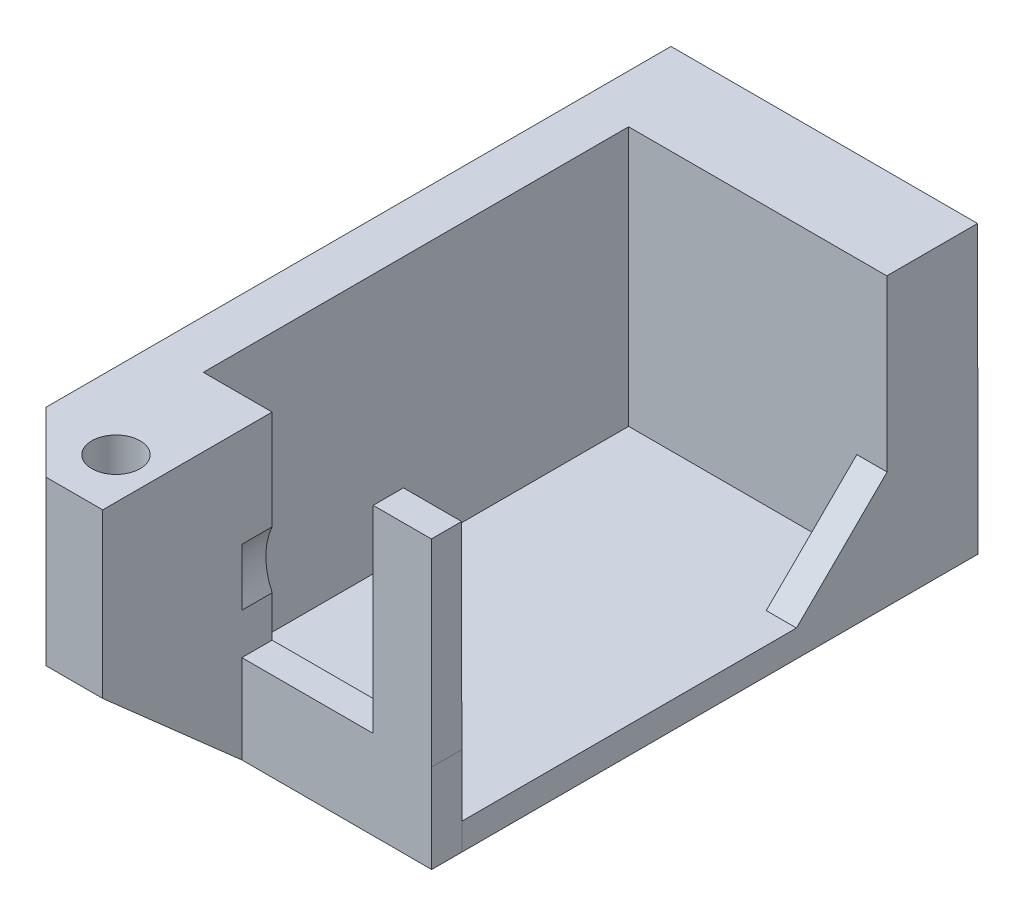
SolidWorks part; units mm, degrees
ref_plane "Alzado" through (0, 0, 0) normal (0, 0, 1) x (1, 0, 0)
ref_plane "Planta" through (0, 0, 0) normal (0, 1, 0) x (1, 0, 0)
ref_plane "Vista lateral" through (0, 0, 0) normal (1, 0, 0) x (0, 0, -1)
sketch "Croquis1" plane through (0, 0, 0) normal (0, 0, 1) x (1, 0, 0)
  line L0 (-10.2002, -11.5) -> (-10.2002, -4.7217)
  line L1 (-10.2002, 4.7217) -> (-10.2002, 21.15)
  line L2 (-10.2002, -11.5) -> (11.5, -11.5)
  line L4 (21.15, -11.5) -> (21.1497, -11.5)
  line L5 (21.1755, -26.15) -> (21.15, -11.5)
  line L6 (21.1243, 21.15) -> (21.1497, -11.5)
  line L7 (21.1755, -26.15) -> (-21.15, -26.15)
  line L8 (11.5, -11.5) -> (11.5, 21.15)
  line L9 (-21.15, -26.15) -> (-29.5751, -26.15)
  line L10 (-29.5751, -26.15) -> (-29.5751, 21.15)
  line L11 (15.9225, 21.15) -> (-15.9225, 21.15) construction
  line L12 (-10.2002, 21.15) -> (-29.5751, 21.15)
  line L13 (11.5, 21.15) -> (21.1243, 21.15)
  arc A0 (-10.2002, -4.7217) -> (-10.2002, 4.7217) centre (0, 0) cw
extrude "Saliente-Extruir1" add sketch "Croquis1" along normal blind 5
sketch "Croquis2" plane through (-29.5751, 0, 0) normal (-1, 0, 0) x (0, 0, 1)
  line L0 (5, 21.15) -> (28, 21.15)
  line L1 (28, 21.15) -> (28, -5.85)
  line L2 (28, -5.85) -> (5, -26.15)
  line L3 (5, -26.15) -> (5, 21.15)
sketch "Croquis3" plane through (0, 21.15, 0) normal (0, 1, 0) x (1, 0, 0)
  circle A0 centre (-17, -19.0131) radius 3.9999
  dimension "D1" = 7.9999
extrude "Saliente-Extruir3" add sketch "Croquis2" against normal up to vertex (19.3749 mm away) up to point (-10.2002, 21.15, 5)
extrude "Cortar-Extruir2" cut sketch "Croquis3" against normal blind 45 contours A0
sketch "Croquis4" plane through (0, 0, 0) normal (0, 0, -1) x (-1, 0, 0)
  line L0 (-21.1755, -26.15) -> (29.5751, -26.15)
  line L1 (29.5751, -26.15) -> (29.5751, 21.15)
  line L2 (29.5751, 21.15) -> (21.5751, 21.15)
  line L3 (10.2002, 21.15) -> (29.5751, 21.15) construction
  line L4 (21.5751, 21.15) -> (21.5751, -21.732)
  line L5 (21.5751, -21.732) -> (-21.1686, -21.732)
  line L7 (-21.1686, -21.732) -> (-21.1755, -26.15)
extrude "Saliente-Extruir4" add sketch "Croquis4" along normal up to vertex (85.3 mm away)
sketch "Croquis5" plane through (0, 0, -85.3) normal (0, 0, -1) x (-1, 0, 0)
  line L0 (-21.1686, -21.732) -> (-21.1022, 21.15)
  line L1 (-21.1243, 21.15) -> (-11.5, 21.15) construction
  line L2 (-21.1022, 21.15) -> (29.5751, 21.15)
  line L3 (29.5751, 21.15) -> (29.5751, -26.15)
  line L4 (29.5751, -26.15) -> (-21.1755, -26.15)
  line L5 (-21.1755, -26.15) -> (-21.1686, -21.732)
extrude "Saliente-Extruir5" add sketch "Croquis5" against normal blind 15
sketch "Croquis7" plane through (21.1349, 0.0327, 0) normal (1, 0.0015, 0) x (0, 0, -1)
  line L0 (70.3, -21.7647) -> (70.3, -6.9399)
  line L1 (70.3, 21.1173) -> (70.3, -21.7647) construction
  line L3 (70.3, -21.7647) -> (55.3, -21.7647)
  line L4 (70.3, -21.7647) -> (0, -21.7647) construction
  line L5 (55.3, -21.7647) -> (70.3, -6.9399)
extrude "Saliente-Extruir6" add sketch "Croquis7" against normal blind 5
chamfer "Chaflán1" distance 10 angle 45 1 edges at (-29.5751, 7.65, 28)
